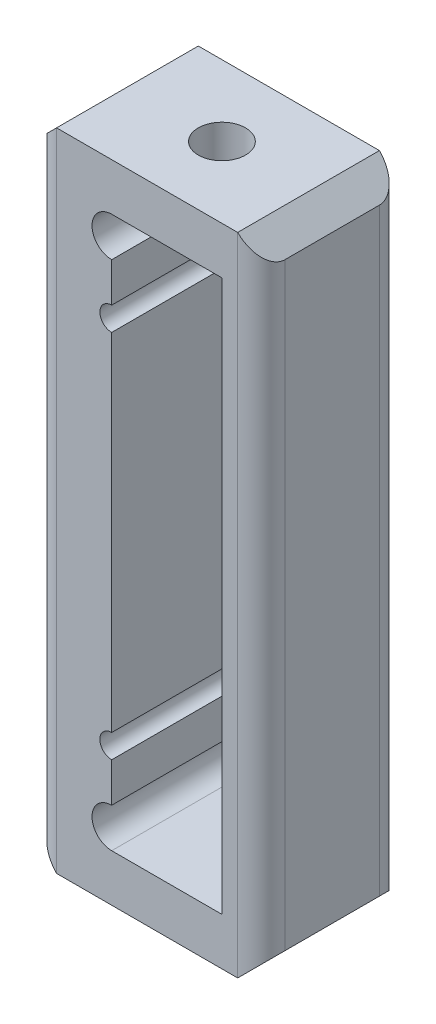
SolidWorks part; units mm, degrees
ref_plane "前视" through (0, 0, 0) normal (0, 0, 1) x (1, 0, 0)
ref_plane "上视" through (0, 0, 0) normal (0, 1, 0) x (1, 0, 0)
ref_plane "右视" through (0, 0, 0) normal (1, 0, 0) x (0, 0, -1)
sketch "草图1" plane through (0, 0, 0) normal (0, 0, 1) x (1, 0, 0)
  line L0 (-3.5051, 5.3246) -> (-3.5051, -64.6754)
  line L1 (-17.5051, -54.6754) -> (-17.5051, -59.6754)
  line L2 (-27.5051, 11.3246) -> (-27.5051, -70.6754)
  line L4 (1.4949, 11.3246) -> (1.4949, -70.6754)
  line L5 (-17.5051, -64.6754) -> (-3.5051, -64.6754)
  line L6 (-17.5051, 0.3246) -> (-17.5051, -4.6754)
  line L7 (-17.5051, 5.3246) -> (-3.5051, 5.3246)
  line L8 (-27.5051, 11.3246) -> (1.4949, 11.3246)
  line L9 (-17.5051, -7.6754) -> (-17.5051, -51.6754)
  line L10 (-27.5051, -70.6754) -> (1.4949, -70.6754)
  arc A0 (-17.5051, 5.3246) -> (-17.5051, 0.3246) centre (-17.5051, 2.8246) ccw
  arc A1 (-17.5051, -4.6754) -> (-17.5051, -7.6754) centre (-17.5051, -6.1754) ccw
  arc A2 (-17.5051, -59.6754) -> (-17.5051, -64.6754) centre (-17.5051, -62.1754) ccw
  arc A3 (-17.5051, -51.6754) -> (-17.5051, -54.6754) centre (-17.5051, -53.1754) ccw
extrude "凸台-拉伸1" add sketch "草图1" along normal blind 18
chamfer "倒角1" distance 3 angle 45 4 edges at (-27.5051, -70.6754, 9) (1.4949, -70.6754, 9) (1.4949, 11.3246, 9) (-27.5051, 11.3246, 9)
fillet "圆角1" radius 3 4 edges at (-27.5051, -29.6754, 0) (-27.5051, -29.6754, 18) (1.4949, -29.6754, 0) (1.4949, -29.6754, 18)
sketch "草图2" plane through (0, -70.6754, 0) normal (0, -1, 0) x (1, 0, 0)
  circle A1 centre (-12.5051, 9) radius 3
extrude "切除-拉伸1" cut sketch "草图2" against normal blind 5
sketch "草图3" plane through (0, 11.3246, 0) normal (0, 1, 0) x (1, 0, 0)
  circle A1 centre (-12.5051, -9) radius 3
extrude "切除-拉伸2" cut sketch "草图3" against normal blind 5
